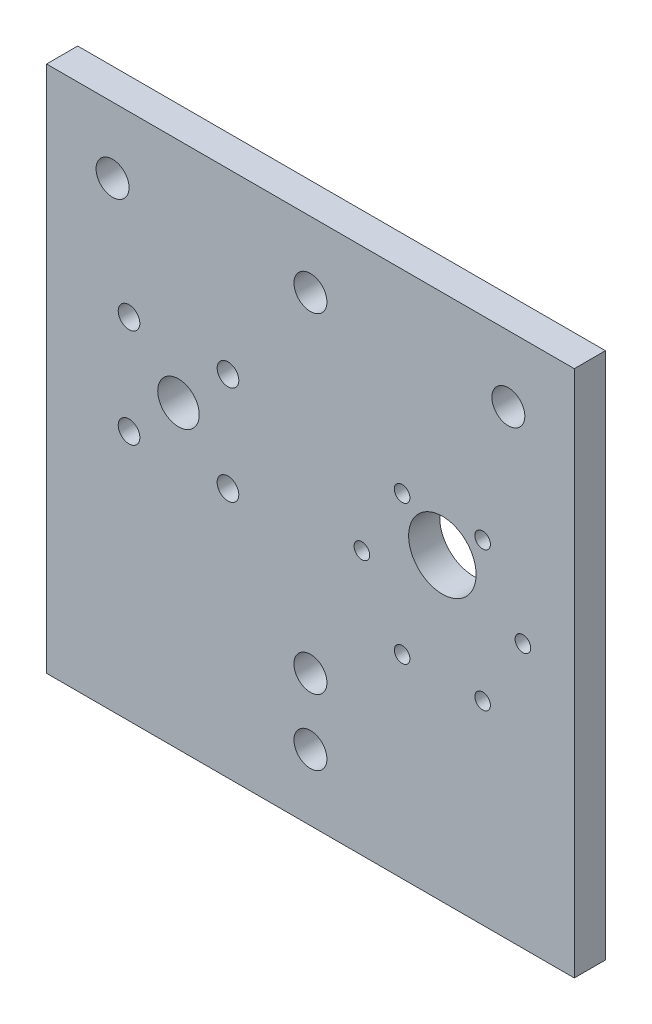
SolidWorks part; units mm, degrees
ref_plane "Front Plane" through (0, 0, 0) normal (0, 0, 1) x (1, 0, 0)
ref_plane "Top Plane" through (0, 0, 0) normal (0, 1, 0) x (1, 0, 0)
ref_plane "Right Plane" through (0, 0, 0) normal (1, 0, 0) x (0, 0, -1)
sketch "Sketch1" plane through (0, 0, 0) normal (0, 0, 1) x (1, 0, 0)
  line L0 (76.2, 50.8) -> (76.2, 0) construction
  line L1 (0, 0) -> (101.6, 0)
  line L2 (0, 0) -> (0, 101.6)
  line L3 (0, 101.6) -> (101.6, 101.6)
  line L4 (101.6, 0) -> (101.6, 101.6)
  line L5 (0, 50.8) -> (120.65, 50.8) construction
  line L6 (76.2, 50.8) -> (108.2013, 106.2279) construction
  line L7 (76.2, 50.8) -> (113.4916, -13.7909) construction
  line L8 (0, 88.9) -> (101.6, 88.9) construction
  line L9 (76.2, 57.8) -> (0, 57.8) construction
  circle A0 centre (76.2, 57.8) radius 6.5
  circle A1 centre (76.2, 50.8) radius 18.5 construction
  circle A2 centre (60.7, 50.8) radius 1.5
  circle A3 centre (91.7, 50.8) radius 1.5
  circle A4 centre (83.95, 37.3766) radius 1.5
  circle A5 centre (68.45, 37.3766) radius 1.5
  circle A6 centre (68.45, 64.2234) radius 1.5
  circle A7 centre (83.95, 64.2234) radius 1.5
  circle A8 centre (76.2, 50.8) radius 15.5 construction
  circle A9 centre (12.7, 88.9) radius 3.175
  circle A10 centre (88.9, 88.9) radius 3.175
  circle A11 centre (25.4, 57.8) radius 4
  circle A12 centre (15.875, 67.325) radius 2.0828
  circle A13 centre (34.925, 67.325) radius 2.0828
  circle A14 centre (34.925, 48.275) radius 2.0828
  circle A15 centre (15.875, 48.275) radius 2.0828
  circle A16 centre (50.8, 88.9) radius 3.175
  circle A17 centre (50.8, 25.4) radius 3.175
  circle A18 centre (50.8, 12.7) radius 3.175
  dimension "D3" = 13
  dimension "D4" = 37
  dimension "D7" = 3
  dimension "D10" = 31
  dimension "D12" = 25.4
  dimension "D15" = 12.7
  dimension "D13" = 6.35
  dimension "D16" = 8
  dimension "D22" = 4.1656
  dimension "D23" = 6.35
  dimension "D1" = 101.6
  dimension "D2" = 101.6
  dimension "D5" = 7
  dimension "D6" = 50.8
  dimension "D8" = 60
  dimension "D9" = 60
  dimension "D11" = 12.7
  dimension "D14" = 12.7
  dimension "D17" = 50.8
  dimension "D18" = 19.05
  dimension "D19" = 19.05
  dimension "D20" = 9.525
  dimension "D21" = 9.525
  dimension "D24" = 12.7
  dimension "D25" = 12.7
  dimension "D26" = 50.8
extrude "Boss-Extrude1" add sketch "Sketch1" along normal blind 5.9944
